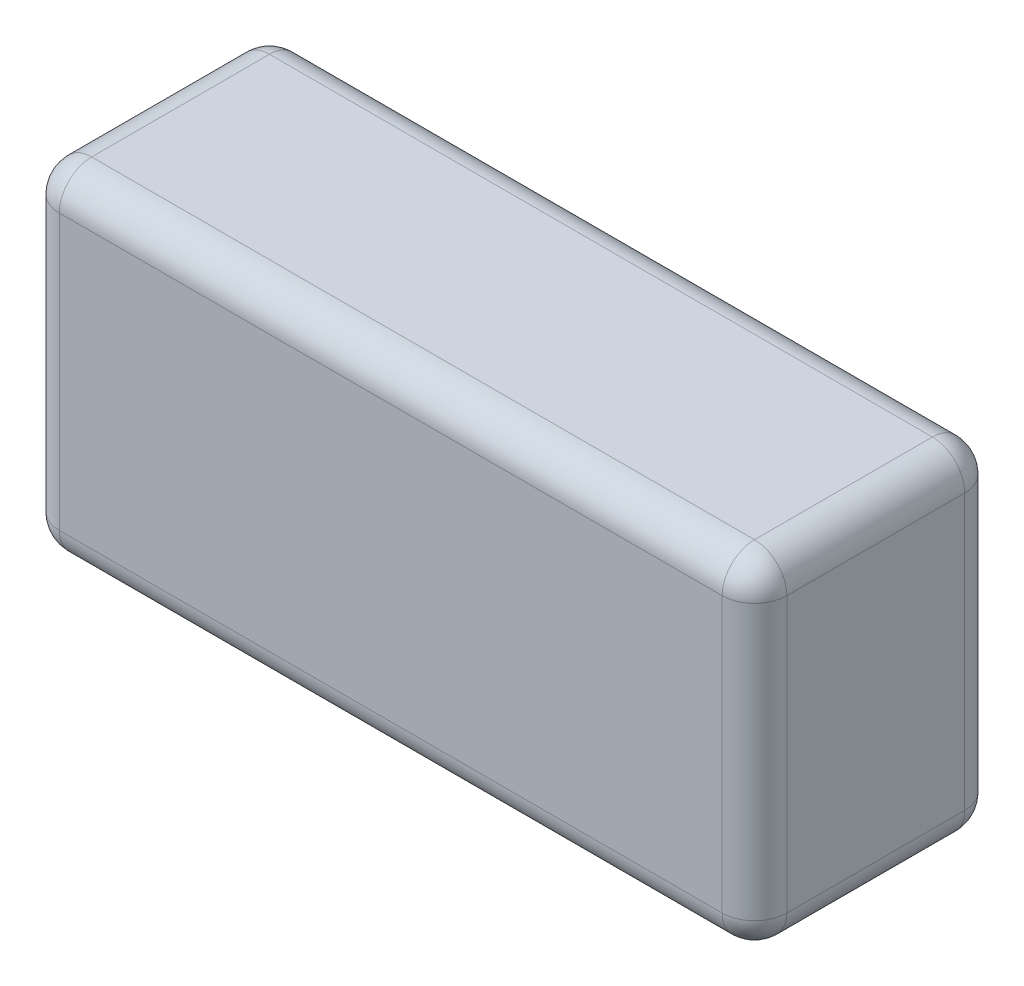
SolidWorks part; units mm, degrees
material "1060 Alloy"
ref_plane "Front Plane" through (0, 0, 0) normal (0, 0, 1) x (1, 0, 0)
ref_plane "Top Plane" through (0, 0, 0) normal (0, 1, 0) x (1, 0, 0)
ref_plane "Right Plane" through (0, 0, 0) normal (1, 0, 0) x (0, 0, -1)
sketch "Sketch1" plane through (0, 0, 0) normal (0, 1, 0) x (1, 0, 0)
  line L1 (-37.5, -12.5) -> (37.5, -12.5)
  line L2 (-37.5, -12.5) -> (-37.5, 12.5)
  line L3 (-37.5, 12.5) -> (37.5, 12.5)
  line L4 (37.5, -12.5) -> (37.5, 12.5)
  line L5 (-37.5, -12.5) -> (37.5, 12.5) construction
  line L6 (-37.5, 12.5) -> (37.5, -12.5) construction
  point P0 (0, 0)
  dimension "D1" = 75
  dimension "D2" = 25
extrude "Boss-Extrude1" add sketch "Sketch1" along normal blind 35
fillet "Fillet1" radius 3.3333 12 edges at (37.5, 17.5, -12.5) (-37.5, 17.5, -12.5) (-37.5, 17.5, 12.5) (37.5, 17.5, 12.5) (0, 35, 12.5) (-37.5, 35, 0) (0, 35, -12.5) (37.5, 35, 0) (0, 0, 12.5) (-37.5, 0, 0) (0, 0, -12.5) (37.5, 0, 0)
